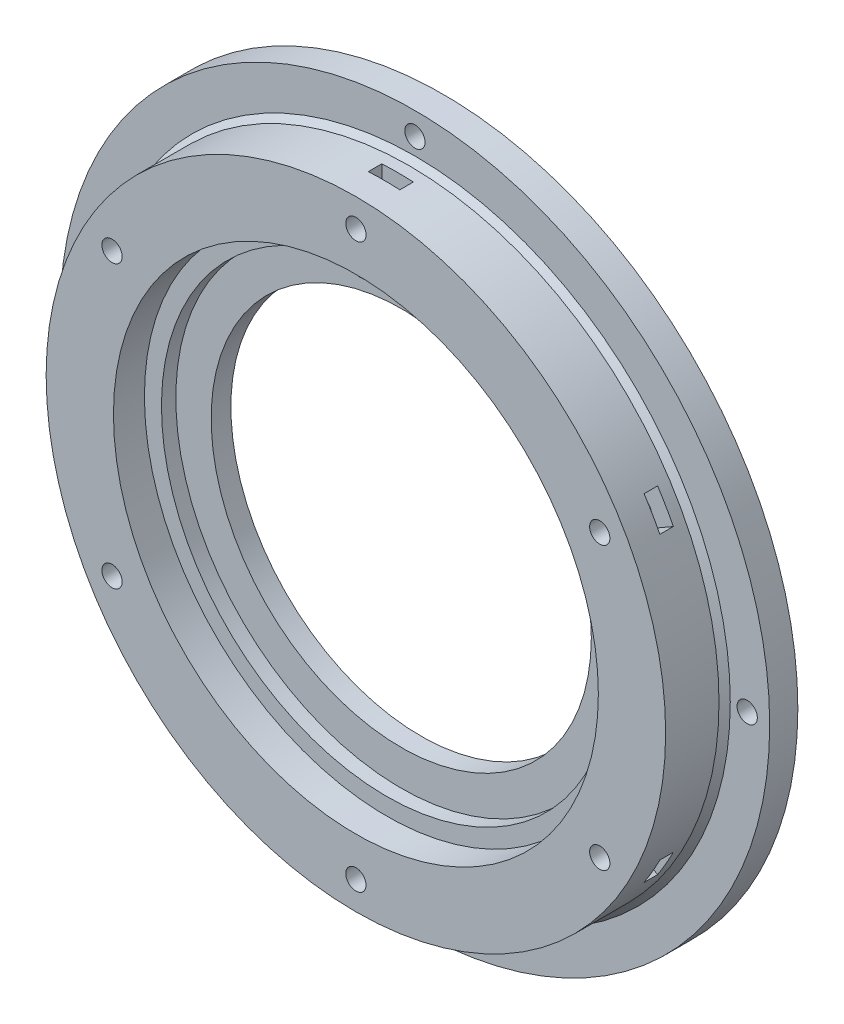
SolidWorks part; units mm, degrees
ref_plane "Front Plane" through (0, 0, 0) normal (0, 0, 1) x (1, 0, 0)
ref_plane "Top Plane" through (0, 0, 0) normal (0, 1, 0) x (1, 0, 0)
ref_plane "Right Plane" through (0, 0, 0) normal (1, 0, 0) x (0, 0, -1)
sketch "Sketch1" plane through (0, 0, 0) normal (0, 1, 0) x (1, 0, 0)
  line L0 (0, -39.8518) -> (0, 55.2469) construction
  line L1 (-67.4266, 0) -> (79.5088, 0) construction
  line L2 (43.05, 0) -> (43.05, 5.5)
  line L3 (43.05, 5.5) -> (40.025, 5.5)
  line L4 (40.025, 5.5) -> (40.025, 8.05)
  line L5 (40.025, 8.05) -> (33.75, 8.05)
  line L6 (33.75, 8.05) -> (33.75, 11.55)
  line L7 (33.75, 11.55) -> (47.85, 11.55)
  line L8 (47.85, 11.55) -> (47.85, 26.05)
  line L9 (47.85, 26.05) -> (33.75, 26.05)
  line L10 (33.75, 26.05) -> (33.75, 31.05)
  line L11 (33.75, 31.05) -> (47.95, 31.05)
  line L12 (55, 31.05) -> (55, 20.475)
  line L13 (55, 0) -> (43.05, 0)
  line L14 (50, -7.9548) -> (50, 44.3819) construction
  line L15 (53.5, 31.05) -> (53.5, 24.05)
  line L16 (53.5, 24.05) -> (50.35, 24.05)
  line L17 (50.35, 24.05) -> (50.35, 29.05)
  line L18 (50.35, 29.05) -> (47.95, 29.05)
  line L19 (47.95, 29.05) -> (47.95, 31.05)
  line L20 (53.5, 31.05) -> (55, 31.05)
  line L21 (-7.0531, 15.475) -> (69.523, 15.475) construction
  line L22 (55, 10.475) -> (63, 10.475)
  line L23 (63, 10.475) -> (63, 20.475)
  line L24 (63, 20.475) -> (55, 20.475)
  line L25 (55, 10.475) -> (55, 0)
  dimension "D1" = 47.85
  dimension "D2" = 14.5
  dimension "D3" = 3.5
  dimension "D4" = 5
  dimension "D5" = 2.55
  dimension "D6" = 5.5
  dimension "D7" = 33.75
  dimension "D8" = 33.75
  dimension "D9" = 40.025
  dimension "D10" = 43.05
  dimension "D11" = 55
  dimension "D12" = 50
  dimension "D13" = 53.5
  dimension "D14" = 3.15
  dimension "D15" = 5
  dimension "D16" = 47.95
  dimension "D17" = 7
  dimension "D18" = 15.475
  dimension "D19" = 76.5761
  dimension "D20" = 8
  dimension "D21" = 10
  dimension "D22" = 5
revolve "Revolve1" add sketch "Sketch1" angle 360 about L0
sketch "Sketch2" plane through (0, 0, 0) normal (0, 0, 1) x (1, 0, 0)
  line L0 (0, 63.3521) -> (0, -60.1897) construction
  circle A0 centre (0, 50) radius 1.8
  circle A1 centre (43.3013, 25) radius 1.8
  circle A2 centre (43.3013, -25) radius 1.8
  circle A3 centre (0, -50) radius 1.8
  circle A4 centre (-43.3013, -25) radius 1.8
  circle A5 centre (-43.3013, 25) radius 1.8
  point P17 (0, 0)
  dimension "D1" = 3.6
  dimension "D2" = 50
  dimension "D3" = 6
extrude "Cut-Extrude1" cut sketch "Sketch2" against normal blind 10
ref_plane "Plane1" through (0, 0, -5) normal (0, 0, 1) x (1, 0, 0)
sketch "Sketch3" plane through (0, 0, -5) normal (0, 0, 1) x (1, 0, 0)
  line L0 (0, 65.4647) -> (0, -62.7269) construction
  line L1 (-2.8, 57.8914) -> (-2.8, 47.2)
  line L2 (-2.8, 47.2) -> (2.8, 47.2)
  line L3 (2.8, 47.2) -> (2.8, 57.8914)
  line L4 (2.8, 57.8914) -> (-2.8, 57.8914)
  line L5 (51.5355, 26.5208) -> (48.7355, 31.3706)
  line L6 (48.7355, 31.3706) -> (39.4764, 26.0249)
  line L7 (39.4764, 26.0249) -> (42.2764, 21.1751)
  line L8 (42.2764, 21.1751) -> (51.5355, 26.5208)
  line L9 (48.7355, -31.3706) -> (51.5355, -26.5208)
  line L10 (51.5355, -26.5208) -> (42.2764, -21.1751)
  line L11 (42.2764, -21.1751) -> (39.4764, -26.0249)
  line L12 (39.4764, -26.0249) -> (48.7355, -31.3706)
  line L13 (-2.8, -57.8914) -> (2.8, -57.8914)
  line L14 (2.8, -57.8914) -> (2.8, -47.2)
  line L15 (2.8, -47.2) -> (-2.8, -47.2)
  line L16 (-2.8, -47.2) -> (-2.8, -57.8914)
  line L17 (-51.5355, -26.5208) -> (-48.7355, -31.3706)
  line L18 (-48.7355, -31.3706) -> (-39.4764, -26.0249)
  line L19 (-39.4764, -26.0249) -> (-42.2764, -21.1751)
  line L20 (-42.2764, -21.1751) -> (-51.5355, -26.5208)
  line L21 (-48.7355, 31.3706) -> (-51.5355, 26.5208)
  line L22 (-51.5355, 26.5208) -> (-42.2764, 21.1751)
  line L23 (-42.2764, 21.1751) -> (-39.4764, 26.0249)
  line L24 (-39.4764, 26.0249) -> (-48.7355, 31.3706)
  circle A0 centre (0, 50) radius 1.8 construction
  point P31 (0, 0)
  dimension "D3" = 2.8
  dimension "D1" = 5.6
  dimension "D2" = 2.8
  dimension "D4" = 6
extrude "Cut-Extrude2" cut sketch "Sketch3" against normal blind 2.4
sketch "Sketch4" plane through (0, 0, -5.5) normal (0, 0, 1) x (1, 0, 0)
  line L0 (0, 77.2348) -> (0, -70.1284) construction
  line L1 (-2.45, 42.9802) -> (-2.45, 39.9499)
  line L2 (2.45, 42.9802) -> (2.45, 39.9499)
  circle A0 centre (0, 0) radius 40.025 construction
  circle A1 centre (0, 0) radius 43.05 construction
  arc A2 (2.45, 39.9499) -> (-2.45, 39.9499) centre (0, 0) ccw
  arc A3 (2.45, 42.9802) -> (-2.45, 42.9802) centre (0, 0) ccw
  point P11 (-2.45, 41.4651)
  dimension "D1" = 2.45
extrude "Boss-Extrude1" add sketch "Sketch4" along normal blind 2.5
sketch "Sketch5" plane through (0, 0, -10.475) normal (0, 0, 1) x (1, 0, 0)
  line L0 (0, 69.6791) -> (0, -69.6791) construction
  circle A0 centre (0, 59) radius 1.8
  circle A1 centre (59, 0) radius 1.8
  circle A2 centre (0, -59) radius 1.8
  circle A3 centre (-59, 0) radius 1.8
  point P14 (0, 0)
  dimension "D1" = 3.6
  dimension "D2" = 59
  dimension "D3" = 4
extrude "Cut-Extrude3" cut sketch "Sketch5" against normal through all
ref_plane "Plane2" through (0, 0, -16.775) normal (0, 0, 1) x (1, 0, 0)
sketch "Sketch6" plane through (0, 0, -16.775) normal (0, 0, 1) x (1, 0, 0)
  line L0 (0, 74.0645) -> (0, -72.5887) construction
  line L1 (-2.8, 66.3687) -> (-2.8, 56.2)
  line L2 (-2.8, 56.2) -> (2.8, 56.2)
  line L3 (-2.8, 66.3687) -> (2.8, 66.3687)
  line L4 (2.8, 66.3687) -> (2.8, 56.2)
  line L5 (66.3687, -2.8) -> (56.2, -2.8)
  line L6 (56.2, 2.8) -> (56.2, -2.8)
  line L7 (66.3687, 2.8) -> (56.2, 2.8)
  line L8 (66.3687, 2.8) -> (66.3687, -2.8)
  line L9 (-2.8, -66.3687) -> (-2.8, -56.2)
  line L10 (2.8, -56.2) -> (-2.8, -56.2)
  line L11 (2.8, -66.3687) -> (2.8, -56.2)
  line L12 (2.8, -66.3687) -> (-2.8, -66.3687)
  line L13 (-66.3687, 2.8) -> (-56.2, 2.8)
  line L14 (-56.2, -2.8) -> (-56.2, 2.8)
  line L15 (-66.3687, -2.8) -> (-56.2, -2.8)
  line L16 (-66.3687, -2.8) -> (-66.3687, 2.8)
  circle A0 centre (0, 59) radius 1.8 construction
  point P24 (0, 0)
  dimension "D1" = 5.6
  dimension "D2" = 2.8
  dimension "D3" = 2.8
  dimension "D4" = 4
extrude "Cut-Extrude4" cut sketch "Sketch6" against normal blind 2.4
sketch "Sketch7" plane through (0, 0, 0) normal (0, 1, 0) x (1, 0, 0)
  line L0 (0, 57.882) -> (0, -19.0921) construction
  line L1 (-86.8096, 0) -> (75.5486, 0) construction
  line L3 (-83.3886, 48.6879) -> (75.5486, 48.6879)
  line L4 (-83.3886, 48.6879) -> (-83.3886, 15.475)
  line L5 (-83.3886, 15.475) -> (75.5486, 15.475)
  line L6 (75.5486, 48.6879) -> (75.5486, 15.475)
  dimension "D1" = 15.475
extrude "Cut-Extrude5" cut sketch "Sketch7" against normal through all both and the other way through all
sketch "Sketch8" plane through (0, 0, -15.475) normal (0, 0, -1) x (-1, 0, 0)
  circle A0 centre (0, 0) radius 52.825
  circle A1 centre (0, 0) radius 50.175
  dimension "D1" = 105.65
  dimension "D2" = 100.35
chamfer "Chamfer1" distance 1 angle 45 1 edges at (55, 0, -10.475)
